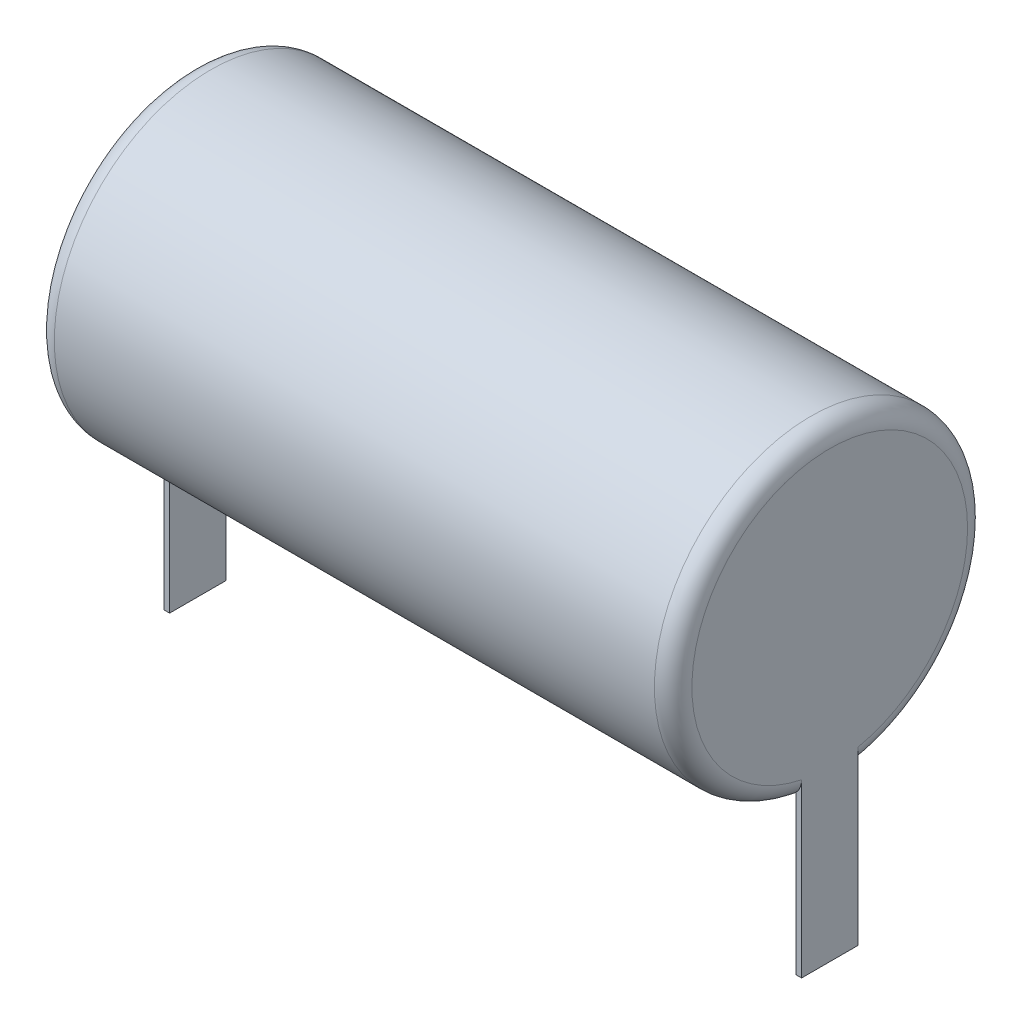
SolidWorks part; units mm, degrees
ref_plane "Спереди" through (0, 0, 0) normal (0, 0, 1) x (1, 0, 0)
ref_plane "Сверху" through (0, 0, 0) normal (0, 1, 0) x (1, 0, 0)
ref_plane "Справа" through (0, 0, 0) normal (1, 0, 0) x (0, 0, -1)
sketch "Эскиз1" plane through (0, 0, 0) normal (1, 0, 0) x (0, 0, -1)
  circle A1 centre (0, 0) radius 8.35
  dimension "D1" = 16.7
extrude "Бобышка-Вытянуть1" add sketch "Эскиз1" along normal mid plane 34
fillet "Скругление1" radius 1 2 edges at (-17, 0, -8.35) (17, 0, -8.35)
sketch "Эскиз2" plane through (17, 0, 0) normal (1, 0, 0) x (0, 0, -1)
  line L0 (0, -1000) -> (0, 49000) construction
  line L2 (-1.5, -16.35) -> (1.5, -16.35)
  line L3 (-1.5, -16.35) -> (-1.5, 0)
  line L4 (-1.5, 0) -> (1.5, 0)
  line L5 (1.5, -16.35) -> (1.5, 0)
  line L6 (-1.5, -16.35) -> (1.5, 0) construction
  line L7 (-1.5, 0) -> (1.5, -16.35) construction
  circle A0 centre (0, 0) radius 8.35 construction
  circle A1 centre (0, 0) radius 8.35 construction
  point P1 (0, -8.175)
  dimension "D1" = 16.7
  dimension "D2" = 16.35
  dimension "D3" = 3
extrude "Бобышка-Вытянуть2" add sketch "Эскиз2" against normal blind 0.3
mirror "Зеркальное отражение1" about plane through (0, 0, 0) normal (1, 0, 0) of "Бобышка-Вытянуть2"
equation "\"D2@Эскиз2\"=8+\"D1@Эскиз2\"/2"
